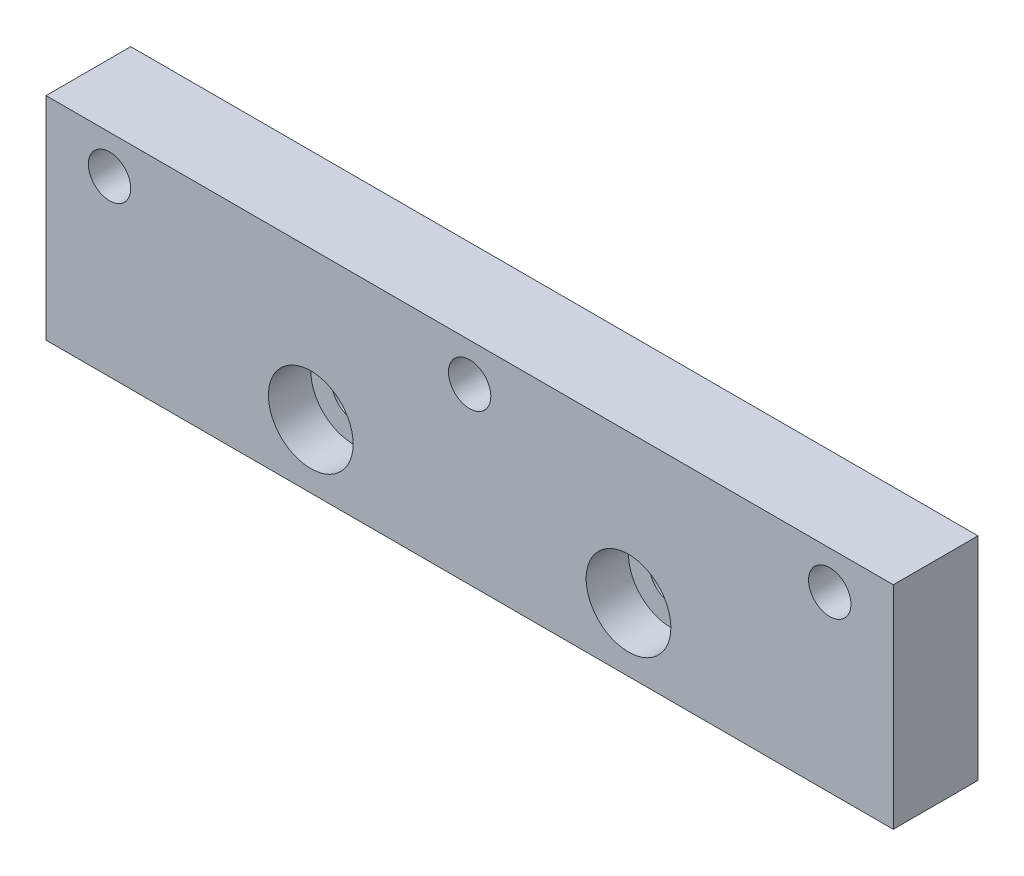
SolidWorks part; units mm, degrees
material "1060 Alloy"
ref_plane "Front Plane" through (0, 0, 0) normal (0, 0, 1) x (1, 0, 0)
ref_plane "Top Plane" through (0, 0, 0) normal (0, 1, 0) x (1, 0, 0)
ref_plane "Right Plane" through (0, 0, 0) normal (1, 0, 0) x (0, 0, -1)
sketch "Sketch2" plane through (0, 0, 0) normal (0, 0, 1) x (1, 0, 0)
  line L1 (-20, 5) -> (20, 5)
  line L2 (-20, 5) -> (-20, -5)
  line L3 (-20, -5) -> (20, -5)
  line L4 (20, 5) -> (20, -5)
  line L5 (-20, 5) -> (20, -5) construction
  line L6 (-20, -5) -> (20, 5) construction
  point P0 (0, 0)
  dimension "D1" = 10
  dimension "D2" = 40
extrude "Boss-Extrude1" add sketch "Sketch2" along normal blind 4
sketch "Sketch3" plane through (0, 0, 4) normal (0, 0, 1) x (1, 0, 0)
  line L1 (0, 5) -> (0, -5) construction
  line L2 (20, 5) -> (-20, 5) construction
  line L3 (-20, -5) -> (20, -5) construction
  line L4 (-7.5, -2) -> (7.5, -2) construction
  circle A0 centre (-17, 3.2) radius 1
  circle A1 centre (0, 3.2) radius 1
  circle A2 centre (17, 3.2) radius 1
  circle A3 centre (-7.5, -2) radius 1
  circle A4 centre (7.5, -2) radius 1
  point P19 (0, -2)
  dimension "D1" = 2
  dimension "D2" = 2
  dimension "D3" = 2
  dimension "D6" = 2
  dimension "D7" = 2
  dimension "D4" = 17
  dimension "D5" = 17
  dimension "D8" = 15
  dimension "D9" = 3
extrude "Cut-Extrude1" cut sketch "Sketch3" against normal through all
sketch "Sketch4" plane through (0, 0, 4) normal (0, 0, 1) x (1, 0, 0)
  circle A0 centre (-7.5, -2) radius 2
  circle A1 centre (7.5, -2) radius 2
  dimension "D1" = 4
  dimension "D2" = 4
extrude "Cut-Extrude2" cut sketch "Sketch4" against normal blind 2
